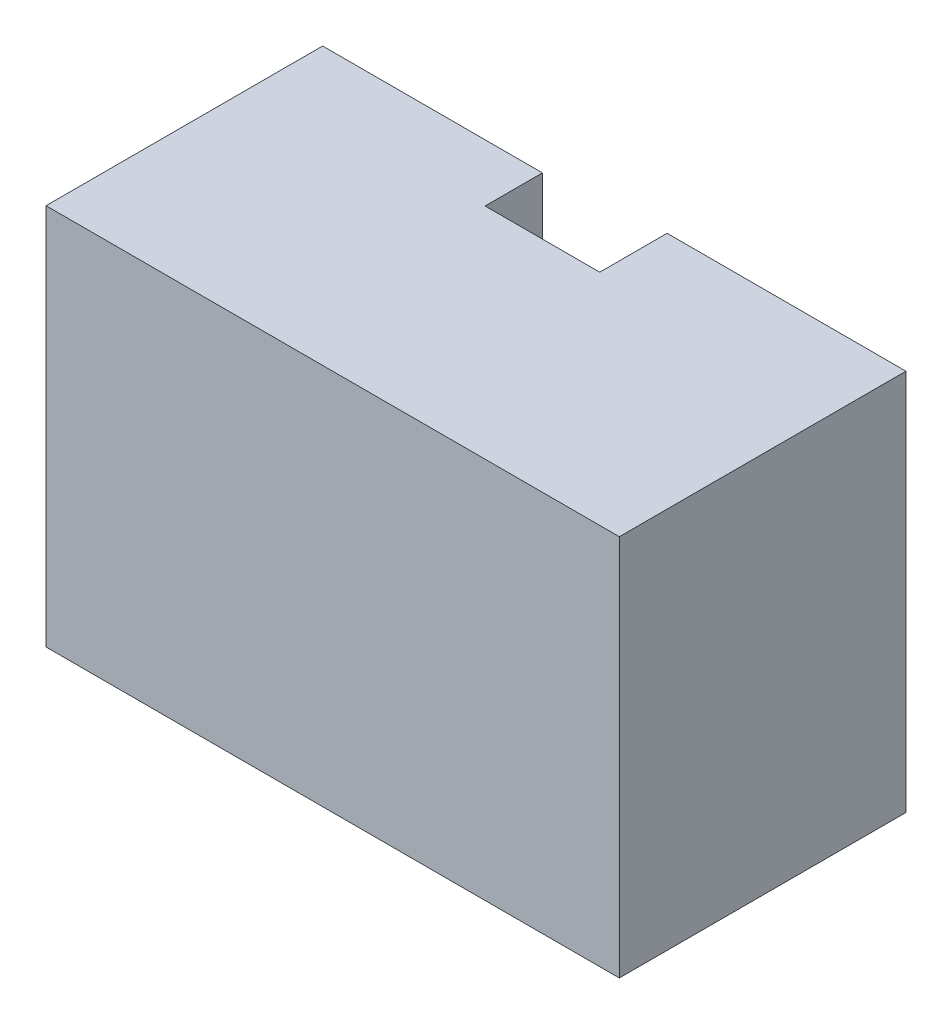
SolidWorks part; units mm, degrees
ref_plane "Спереди" through (0, 0, 0) normal (0, 0, 1) x (1, 0, 0)
ref_plane "Сверху" through (0, 0, 0) normal (0, 1, 0) x (1, 0, 0)
ref_plane "Справа" through (0, 0, 0) normal (1, 0, 0) x (0, 0, -1)
sketch "Эскиз1" plane through (0, 0, 0) normal (0, 1, 0) x (1, 0, 0)
  line L0 (90, 289.5) -> (230, 289.5)
  line L1 (230, 289.5) -> (230, 229.5)
  line L2 (230, 229.5) -> (350, 229.5)
  line L3 (350, 229.5) -> (350, 300)
  line L4 (350, 300) -> (600, 300)
  line L5 (600, 300) -> (600, 0)
  line L6 (600, 0) -> (100, 0)
  line L7 (100, 0) -> (0, 0)
  line L8 (0, 0) -> (0, 289.5)
  line L9 (0, 289.5) -> (90, 289.5)
extrude "Бобышка-Вытянуть1" add sketch "Эскиз1" along normal mid plane 400
